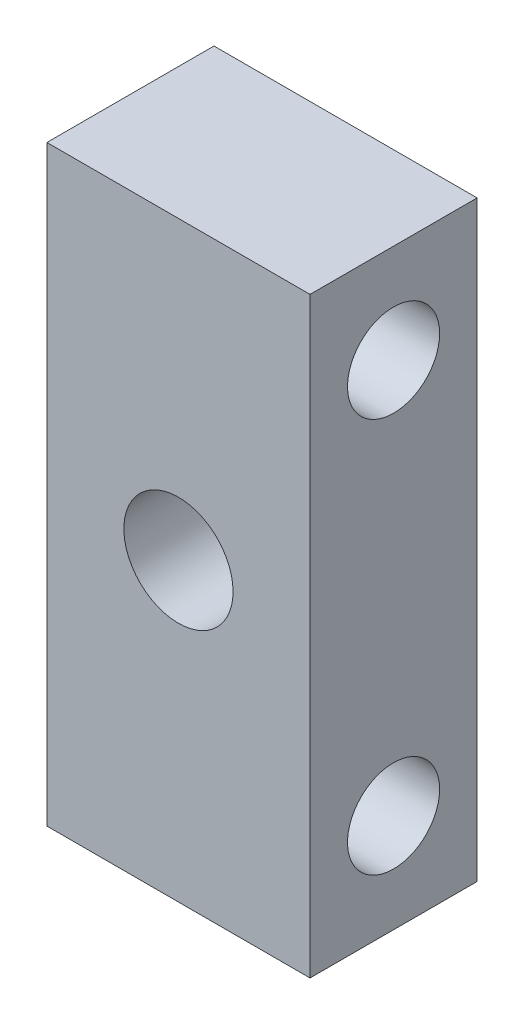
SolidWorks part; units mm, degrees
ref_plane "Front Plane" through (0, 0, 0) normal (0, 0, 1) x (1, 0, 0)
ref_plane "Top Plane" through (0, 0, 0) normal (0, 1, 0) x (1, 0, 0)
ref_plane "Right Plane" through (0, 0, 0) normal (1, 0, 0) x (0, 0, -1)
sketch "Sketch1" plane through (0, 0, 0) normal (0, 0, 1) x (1, 0, 0)
  line L5 (10, 22.5) -> (-10, 22.5)
  line L6 (10, 22.5) -> (10, -22.5)
  line L7 (10, -22.5) -> (-10, -22.5)
  line L8 (-10, 22.5) -> (-10, -22.5)
  line L9 (0, -22.5) -> (0, 22.5) construction
  line L10 (10, 0) -> (-10, 0) construction
  point P0 (0, 0)
  point P1 (0, 0)
  dimension "D1" = 45
  dimension "D2" = 20
extrude "Boss-Extrude1" add sketch "Sketch1" along normal blind 12.7
sketch "Sketch2" plane through (0, 0, 12.7) normal (0, 0, 1) x (1, 0, 0)
  circle A0 centre (0, 0) radius 4.15
extrude "Cut-Extrude1" cut sketch "Sketch2" against normal through all
sketch "Sketch3" plane through (10, 0, 0) normal (1, 0, 0) x (0, 0, -1)
  circle A0 centre (-6.35, 15) radius 3.5
  circle A1 centre (-6.35, -15) radius 3.5
extrude "Cut-Extrude2" cut sketch "Sketch3" against normal through all
